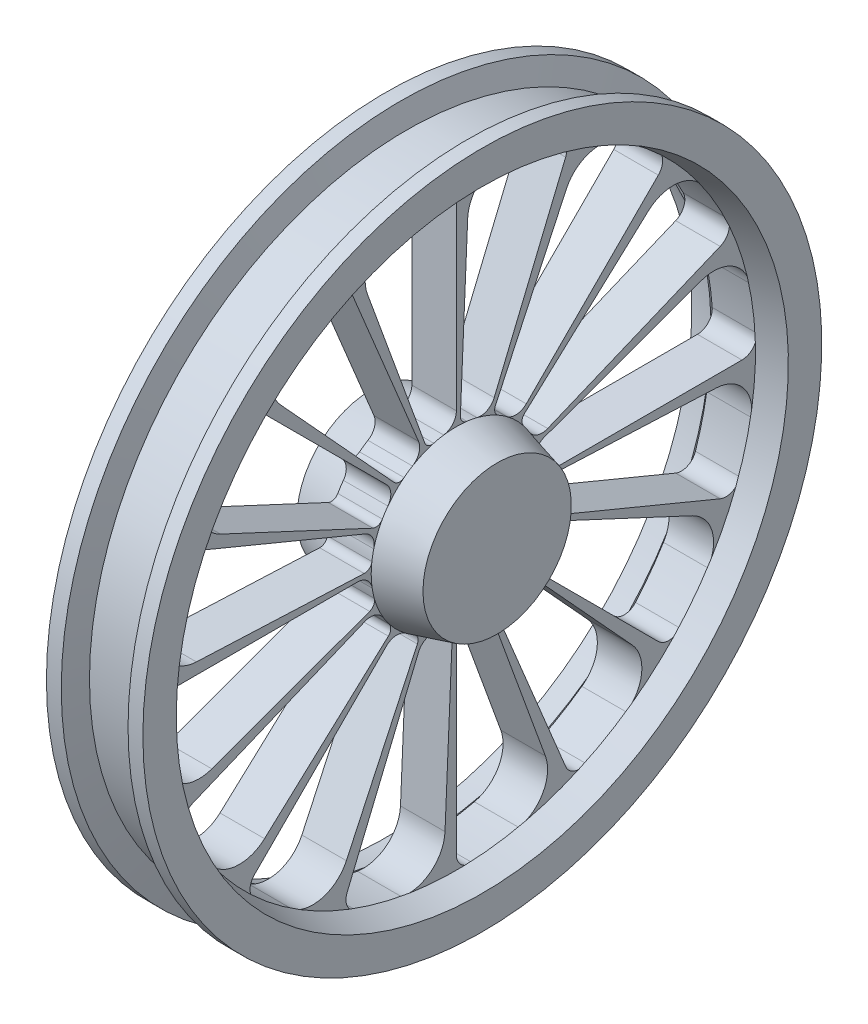
SolidWorks part; units mm, degrees
material "1060 Alloy"
ref_plane "Front Plane" through (0, 0, 0) normal (0, 0, 1) x (1, 0, 0)
ref_plane "Top Plane" through (0, 0, 0) normal (0, 1, 0) x (1, 0, 0)
ref_plane "Right Plane" through (0, 0, 0) normal (1, 0, 0) x (0, 0, -1)
sketch "Sketch1" plane through (0, 0, 0) normal (0, 1, 0) x (1, 0, 0)
  line L0 (0, 0) -> (170, 0) construction
  line L1 (85, 0) -> (85, 885) construction
  line L2 (0, 0) -> (0, 100)
  line L3 (0, 100) -> (55, 114.7372)
  line L4 (55, 114.7372) -> (55, 403.1218)
  line L5 (55, 403.1218) -> (20, 412.5)
  line L6 (20, 412.5) -> (20, 457.5)
  line L7 (20, 457.5) -> (40, 457.5)
  line L8 (40, 457.5) -> (48.0385, 427.5)
  line L9 (130, 457.5) -> (121.9615, 427.5)
  line L10 (150, 457.5) -> (130, 457.5)
  line L11 (150, 412.5) -> (150, 457.5)
  line L12 (115, 403.1218) -> (150, 412.5)
  line L13 (115, 114.7372) -> (115, 403.1218)
  line L14 (170, 100) -> (115, 114.7372)
  line L15 (170, 0) -> (170, 100)
  line L16 (48.0385, 427.5) -> (121.9615, 427.5)
  line L17 (0, 0) -> (170, 0)
  dimension "D1" = 100
  dimension "D2" = 15
  dimension "D3" = 15
  dimension "D4" = 170
  dimension "D5" = 457.5
  dimension "D6" = 45
  dimension "D7" = 20
  dimension "D8" = 30
  dimension "D9" = 60
  dimension "D10" = 130
revolve "Revolve1" add sketch "Sketch1" angle 360 about L17
sketch "Sketch2" plane through (55, 0, 0) normal (-1, 0, 0) x (0, 0, 1)
  line L0 (0, 133.2446) -> (0, 384.9073)
  line L1 (0, 0) -> (137.8758, 378.8106) construction
  line L2 (42.5253, 116.8374) -> (119.9385, 329.5282)
  line L3 (84, 91.6699) -> (236.9137, 258.5459)
  line L4 (50.9905, 123.1019) -> (147.2977, 355.608)
  line L5 (112.6864, 52.5465) -> (317.821, 148.2023)
  line L6 (94.2181, 94.2181) -> (272.1706, 272.1706)
  line L7 (124.2174, 5.4234) -> (350.3429, 15.2963)
  line L8 (123.1019, 50.9905) -> (355.608, 147.2977)
  line L9 (116.8374, -42.5253) -> (329.5282, -119.9385)
  line L10 (133.2446, 0) -> (384.9073, 0)
  line L11 (91.6699, -84) -> (258.5459, -236.9137)
  line L12 (123.1019, -50.9905) -> (355.608, -147.2977)
  line L13 (52.5465, -112.6864) -> (148.2023, -317.821)
  line L14 (94.2181, -94.2181) -> (272.1706, -272.1706)
  line L15 (5.4234, -124.2174) -> (15.2963, -350.3429)
  line L16 (50.9905, -123.1019) -> (147.2977, -355.608)
  line L17 (-42.5253, -116.8374) -> (-119.9385, -329.5282)
  line L18 (0, -133.2446) -> (0, -384.9073)
  line L19 (-84, -91.6699) -> (-236.9137, -258.5459)
  line L20 (-50.9905, -123.1019) -> (-147.2977, -355.608)
  line L21 (-112.6864, -52.5465) -> (-317.821, -148.2023)
  line L22 (-94.2181, -94.2181) -> (-272.1706, -272.1706)
  line L23 (-124.2174, -5.4234) -> (-350.3429, -15.2963)
  line L24 (-123.1019, -50.9905) -> (-355.608, -147.2977)
  line L25 (-116.8374, 42.5253) -> (-329.5282, 119.9385)
  line L26 (-133.2446, 0) -> (-384.9073, 0)
  line L27 (-91.6699, 84) -> (-258.5459, 236.9137)
  line L28 (-123.1019, 50.9905) -> (-355.608, 147.2977)
  line L29 (-52.5465, 112.6864) -> (-148.2023, 317.821)
  line L30 (-94.2181, 94.2181) -> (-272.1706, 272.1706)
  line L31 (-5.4234, 124.2174) -> (-15.2963, 350.3429)
  line L32 (-50.9905, 123.1019) -> (-147.2977, 355.608)
  circle A0 centre (0, 0) radius 114.7372 construction
  circle A1 centre (0, 0) radius 403.1218 construction
  arc A2 (17.0313, 113.4661) -> (30.4725, 110.6167) centre (0, 0) cw
  arc A4 (0, 133.2446) -> (17.0313, 113.4661) centre (20, 133.2446) ccw
  arc A5 (0, 384.9073) -> (21.4288, 404.8562) centre (20, 384.9073) cw
  arc A6 (42.5253, 116.8374) -> (30.4725, 110.6167) centre (33.1284, 120.2576) cw
  arc A7 (21.4288, 404.8562) -> (84.3273, 395.3185) centre (-7.3706, 2.7645) cw
  arc A8 (84.3273, 395.3185) -> (119.9385, 329.5282) centre (72.9538, 346.6292) cw
  arc A9 (174.7294, 365.8379) -> (229.1901, 332.956) centre (-5.7516, 5.3747) cw
  arc A10 (229.1901, 332.956) -> (236.9137, 258.5459) centre (200.0498, 292.3254) cw
  arc A11 (84, 91.6699) -> (70.4841, 90.5352) centre (76.6272, 98.4258) cw
  arc A12 (59.1564, 98.3115) -> (70.4841, 90.5352) centre (0, 0) cw
  arc A13 (50.9905, 123.1019) -> (59.1564, 98.3115) centre (69.4681, 115.4483) ccw
  arc A14 (147.2977, 355.608) -> (174.7294, 365.8379) centre (165.7752, 347.9543) cw
  arc A15 (301.429, 271.1241) -> (339.1608, 219.904) centre (-3.257, 7.1666) cw
  arc A16 (339.1608, 219.904) -> (317.821, 148.2023) centre (296.69, 193.5177) cw
  arc A17 (112.6864, 52.5465) -> (99.7651, 56.6705) centre (108.4602, 61.6096) cw
  arc A18 (92.2756, 68.1898) -> (99.7651, 56.6705) centre (0, 0) cw
  arc A19 (94.2181, 94.2181) -> (92.2756, 68.1898) centre (108.3603, 80.076) ccw
  arc A20 (272.1706, 272.1706) -> (301.429, 271.1241) centre (286.3127, 258.0284) cw
  arc A21 (382.2388, 135.1341) -> (397.4973, 73.3736) centre (-0.2666, 7.8675) cw
  arc A22 (397.4973, 73.3736) -> (350.3429, 15.2963) centre (348.1619, 65.2487) cw
  arc A23 (124.2174, 5.4234) -> (113.8578, 14.1782) centre (123.7812, 15.4139) cw
  arc A24 (111.3466, 27.6868) -> (113.8578, 14.1782) centre (0, 0) cw
  arc A25 (123.1019, 50.9905) -> (111.3466, 27.6868) centre (130.7556, 32.5129) ccw
  arc A26 (355.608, 147.2977) -> (382.2388, 135.1341) centre (363.2617, 128.8201) cw
  arc A27 (404.8562, -21.4288) -> (395.3185, -84.3273) centre (2.7645, 7.3706) cw
  arc A28 (395.3185, -84.3273) -> (329.5282, -119.9385) centre (346.6292, -72.9538) cw
  arc A29 (116.8374, -42.5253) -> (110.6167, -30.4725) centre (120.2576, -33.1284) cw
  arc A30 (113.4661, -17.0313) -> (110.6167, -30.4725) centre (0, 0) cw
  arc A31 (133.2446, 0) -> (113.4661, -17.0313) centre (133.2446, -20) ccw
  arc A32 (384.9073, 0) -> (404.8562, -21.4288) centre (384.9073, -20) cw
  arc A33 (365.8379, -174.7294) -> (332.956, -229.1901) centre (5.3747, 5.7516) cw
  arc A34 (332.956, -229.1901) -> (258.5459, -236.9137) centre (292.3254, -200.0498) cw
  arc A35 (91.6699, -84) -> (90.5352, -70.4841) centre (98.4258, -76.6272) cw
  arc A36 (98.3115, -59.1564) -> (90.5352, -70.4841) centre (0, 0) cw
  arc A37 (123.1019, -50.9905) -> (98.3115, -59.1564) centre (115.4483, -69.4681) ccw
  arc A38 (355.608, -147.2977) -> (365.8379, -174.7294) centre (347.9543, -165.7752) cw
  arc A39 (271.1241, -301.429) -> (219.904, -339.1608) centre (7.1666, 3.257) cw
  arc A40 (219.904, -339.1608) -> (148.2023, -317.821) centre (193.5177, -296.69) cw
  arc A41 (52.5465, -112.6864) -> (56.6705, -99.7651) centre (61.6096, -108.4602) cw
  arc A42 (68.1898, -92.2756) -> (56.6705, -99.7651) centre (0, 0) cw
  arc A43 (94.2181, -94.2181) -> (68.1898, -92.2756) centre (80.076, -108.3603) ccw
  arc A44 (272.1706, -272.1706) -> (271.1241, -301.429) centre (258.0284, -286.3127) cw
  arc A45 (135.1341, -382.2388) -> (73.3736, -397.4973) centre (7.8675, 0.2666) cw
  arc A46 (73.3736, -397.4973) -> (15.2963, -350.3429) centre (65.2487, -348.1619) cw
  arc A47 (5.4234, -124.2174) -> (14.1782, -113.8578) centre (15.4139, -123.7812) cw
  arc A48 (27.6868, -111.3466) -> (14.1782, -113.8578) centre (0, 0) cw
  arc A49 (50.9905, -123.1019) -> (27.6868, -111.3466) centre (32.5129, -130.7556) ccw
  arc A50 (147.2977, -355.608) -> (135.1341, -382.2388) centre (128.8201, -363.2617) cw
  arc A51 (-21.4288, -404.8562) -> (-84.3273, -395.3185) centre (7.3706, -2.7645) cw
  arc A52 (-84.3273, -395.3185) -> (-119.9385, -329.5282) centre (-72.9538, -346.6292) cw
  arc A53 (-42.5253, -116.8374) -> (-30.4725, -110.6167) centre (-33.1284, -120.2576) cw
  arc A54 (-17.0313, -113.4661) -> (-30.4725, -110.6167) centre (0, 0) cw
  arc A55 (0, -133.2446) -> (-17.0313, -113.4661) centre (-20, -133.2446) ccw
  arc A56 (0, -384.9073) -> (-21.4288, -404.8562) centre (-20, -384.9073) cw
  arc A57 (-174.7294, -365.8379) -> (-229.1901, -332.956) centre (5.7516, -5.3747) cw
  arc A58 (-229.1901, -332.956) -> (-236.9137, -258.5459) centre (-200.0498, -292.3254) cw
  arc A59 (-84, -91.6699) -> (-70.4841, -90.5352) centre (-76.6272, -98.4258) cw
  arc A60 (-59.1564, -98.3115) -> (-70.4841, -90.5352) centre (0, 0) cw
  arc A61 (-50.9905, -123.1019) -> (-59.1564, -98.3115) centre (-69.4681, -115.4483) ccw
  arc A62 (-147.2977, -355.608) -> (-174.7294, -365.8379) centre (-165.7752, -347.9543) cw
  arc A63 (-301.429, -271.1241) -> (-339.1608, -219.904) centre (3.257, -7.1666) cw
  arc A64 (-339.1608, -219.904) -> (-317.821, -148.2023) centre (-296.69, -193.5177) cw
  arc A65 (-112.6864, -52.5465) -> (-99.7651, -56.6705) centre (-108.4602, -61.6096) cw
  arc A66 (-92.2756, -68.1898) -> (-99.7651, -56.6705) centre (0, 0) cw
  arc A67 (-94.2181, -94.2181) -> (-92.2756, -68.1898) centre (-108.3603, -80.076) ccw
  arc A68 (-272.1706, -272.1706) -> (-301.429, -271.1241) centre (-286.3127, -258.0284) cw
  arc A69 (-382.2388, -135.1341) -> (-397.4973, -73.3736) centre (0.2666, -7.8675) cw
  arc A70 (-397.4973, -73.3736) -> (-350.3429, -15.2963) centre (-348.1619, -65.2487) cw
  arc A71 (-124.2174, -5.4234) -> (-113.8578, -14.1782) centre (-123.7812, -15.4139) cw
  arc A72 (-111.3466, -27.6868) -> (-113.8578, -14.1782) centre (0, 0) cw
  arc A73 (-123.1019, -50.9905) -> (-111.3466, -27.6868) centre (-130.7556, -32.5129) ccw
  arc A74 (-355.608, -147.2977) -> (-382.2388, -135.1341) centre (-363.2617, -128.8201) cw
  arc A75 (-404.8562, 21.4288) -> (-395.3185, 84.3273) centre (-2.7645, -7.3706) cw
  arc A76 (-395.3185, 84.3273) -> (-329.5282, 119.9385) centre (-346.6292, 72.9538) cw
  arc A77 (-116.8374, 42.5253) -> (-110.6167, 30.4725) centre (-120.2576, 33.1284) cw
  arc A78 (-113.4661, 17.0313) -> (-110.6167, 30.4725) centre (0, 0) cw
  arc A79 (-133.2446, 0) -> (-113.4661, 17.0313) centre (-133.2446, 20) ccw
  arc A80 (-384.9073, 0) -> (-404.8562, 21.4288) centre (-384.9073, 20) cw
  arc A81 (-365.8379, 174.7294) -> (-332.956, 229.1901) centre (-5.3747, -5.7516) cw
  arc A82 (-332.956, 229.1901) -> (-258.5459, 236.9137) centre (-292.3254, 200.0498) cw
  arc A83 (-91.6699, 84) -> (-90.5352, 70.4841) centre (-98.4258, 76.6272) cw
  arc A84 (-98.3115, 59.1564) -> (-90.5352, 70.4841) centre (0, 0) cw
  arc A85 (-123.1019, 50.9905) -> (-98.3115, 59.1564) centre (-115.4483, 69.4681) ccw
  arc A86 (-355.608, 147.2977) -> (-365.8379, 174.7294) centre (-347.9543, 165.7752) cw
  arc A87 (-271.1241, 301.429) -> (-219.904, 339.1608) centre (-7.1666, -3.257) cw
  arc A88 (-219.904, 339.1608) -> (-148.2023, 317.821) centre (-193.5177, 296.69) cw
  arc A89 (-52.5465, 112.6864) -> (-56.6705, 99.7651) centre (-61.6096, 108.4602) cw
  arc A90 (-68.1898, 92.2756) -> (-56.6705, 99.7651) centre (0, 0) cw
  arc A91 (-94.2181, 94.2181) -> (-68.1898, 92.2756) centre (-80.076, 108.3603) ccw
  arc A92 (-272.1706, 272.1706) -> (-271.1241, 301.429) centre (-258.0284, 286.3127) cw
  arc A93 (-135.1341, 382.2388) -> (-73.3736, 397.4973) centre (-7.8675, -0.2666) cw
  arc A94 (-73.3736, 397.4973) -> (-15.2963, 350.3429) centre (-65.2487, 348.1619) cw
  arc A95 (-5.4234, 124.2174) -> (-14.1782, 113.8578) centre (-15.4139, 123.7812) cw
  arc A96 (-27.6868, 111.3466) -> (-14.1782, 113.8578) centre (0, 0) cw
  arc A97 (-50.9905, 123.1019) -> (-27.6868, 111.3466) centre (-32.5129, 130.7556) ccw
  arc A98 (-147.2977, 355.608) -> (-135.1341, 382.2388) centre (-128.8201, 363.2617) cw
  point P15 (0, 114.7372)
  point P18 (0, 403.1218)
  point P20 (39.2424, 107.8177)
  point P222 (0, 0)
  dimension "D2" = 20
  dimension "D3" = 10
  dimension "D4" = 50
  dimension "D1" = 20
  dimension "D5" = 16
extrude "Cut-Extrude1" cut sketch "Sketch2" against normal blind 60
equation "\"A\"= 130mm"
equation "\"B\"= 915mm"
